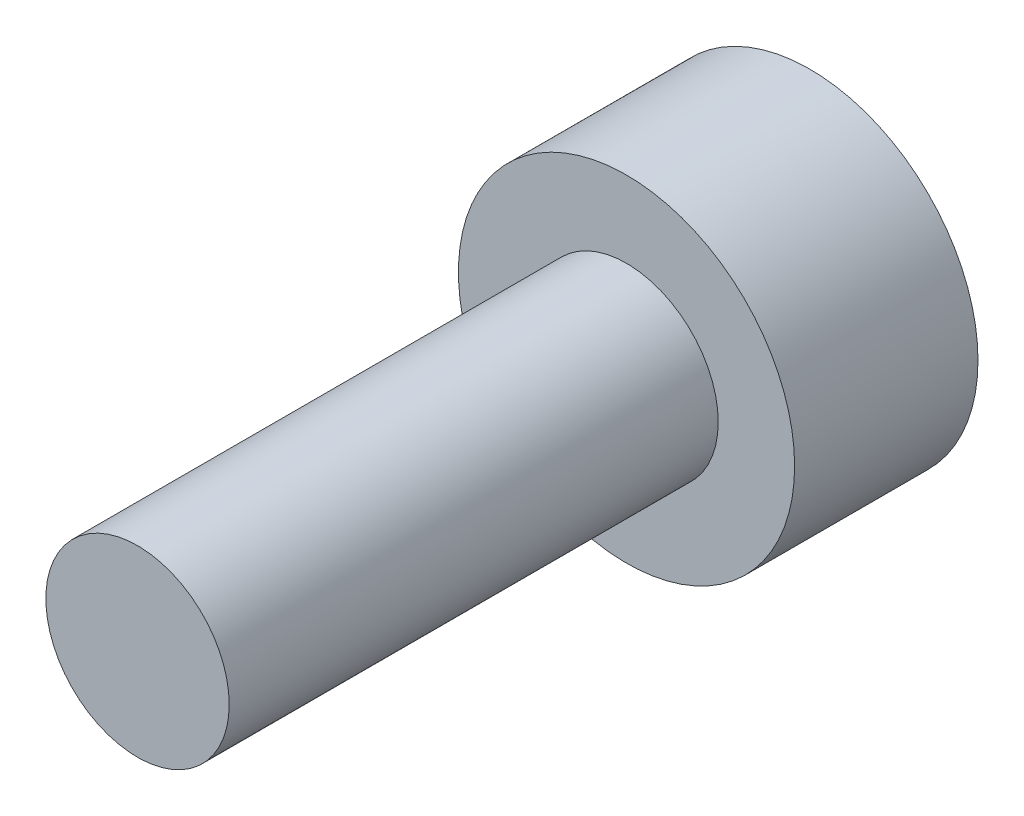
SolidWorks part; units mm, degrees
material "Acero aleado"
ref_plane "Alzado" through (0, 0, 0) normal (0, 0, 1) x (1, 0, 0)
ref_plane "Planta" through (0, 0, 0) normal (0, 1, 0) x (1, 0, 0)
ref_plane "Vista lateral" through (0, 0, 0) normal (1, 0, 0) x (0, 0, -1)
sketch "Croquis1" plane through (0, 0, 0) normal (0, 0, 1) x (1, 0, 0)
  circle A0 centre (0, 0) radius 2.75
  dimension "D1" = 5.5
extrude "Cabeza" add sketch "Croquis1" along normal blind 3 from offset 3
sketch "Croquis2" plane through (0, 0, 0) normal (0, 0, 1) x (1, 0, 0)
  circle A0 centre (0, 0) radius 1.5
  dimension "D1" = 3
extrude "Cuerpo" add sketch "Croquis2" along normal blind 8
sketch "Croquis3" plane through (0, 0, 0) normal (0, 0, 1) x (1, 0, 0)
  line L0 (1.4434, 0) -> (0.7217, 1.25)
  line L1 (0.7217, 1.25) -> (-0.7217, 1.25)
  line L2 (-0.7217, 1.25) -> (-1.4434, 0)
  line L3 (-1.4434, 0) -> (-0.7217, -1.25)
  line L4 (-0.7217, -1.25) -> (0.7217, -1.25)
  line L5 (0.7217, -1.25) -> (1.4434, 0)
  dimension "D1" = 1.4434
  dimension "D2" = 0.7217
  dimension "D3" = 1.25
  dimension "D4" = 0.7217
  dimension "D5" = 1.25
  dimension "D6" = 1.4434
  dimension "D7" = 0.7217
  dimension "D8" = 1.25
  dimension "D9" = 0.7217
  dimension "D10" = 1.25
extrude "Hexagono_interior" cut sketch "Croquis3" along normal blind 1.3 from offset 3
